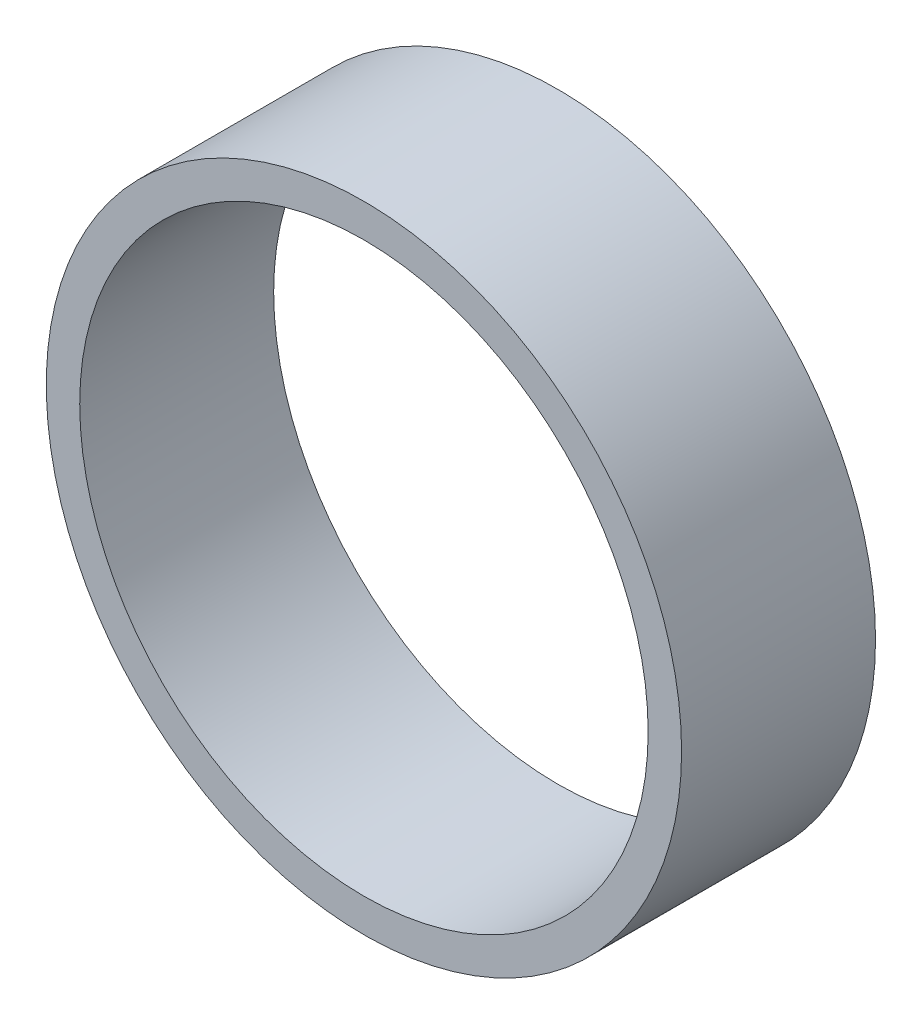
SolidWorks part; units mm, degrees
ref_plane "Front Plane" through (0, 0, 0) normal (0, 0, 1) x (1, 0, 0)
ref_plane "Top Plane" through (0, 0, 0) normal (0, 1, 0) x (1, 0, 0)
ref_plane "Right Plane" through (0, 0, 0) normal (1, 0, 0) x (0, 0, -1)
sketch "Sketch1" plane through (0, 0, 0) normal (0, 0, 1) x (1, 0, 0)
  circle A0 centre (-43.2127, 1.4419) radius 9.5
  dimension "D1" = 19
extrude "Boss-Extrude1" add sketch "Sketch1" along normal blind 5.8
sketch "Sketch2" plane through (0, 0, 5.8) normal (0, 0, 1) x (1, 0, 0)
  circle A0 centre (-43.2127, 1.4419) radius 8.5
  dimension "D1" = 17
extrude "Cut-Extrude1" cut sketch "Sketch2" against normal blind 5.8
